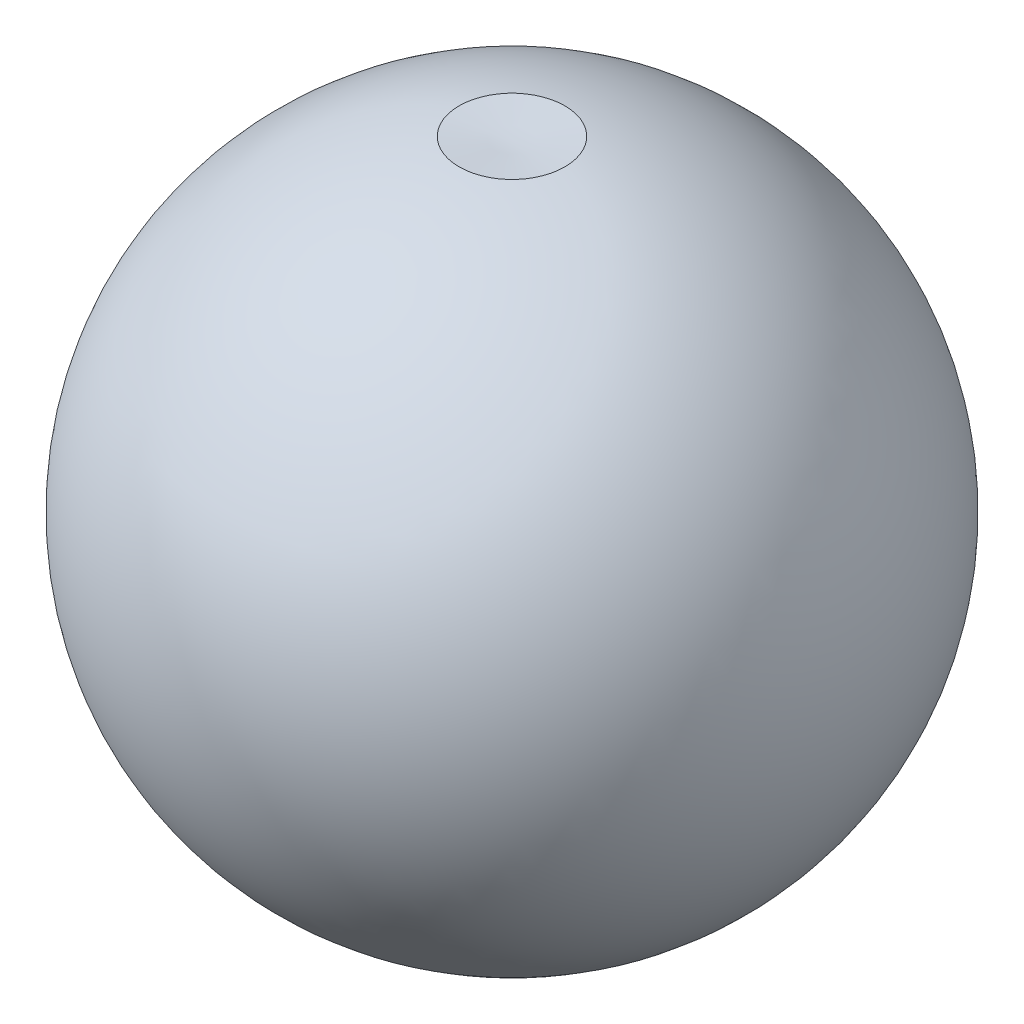
SolidWorks part; units mm, degrees
ref_plane "Plan de face" through (0, 0, 0) normal (0, 0, 1) x (1, 0, 0)
ref_plane "Plan de dessus" through (0, 0, 0) normal (0, 1, 0) x (1, 0, 0)
ref_plane "Plan de droite" through (0, 0, 0) normal (1, 0, 0) x (0, 0, -1)
sketch "Esquisse1" plane through (0, 0, 0) normal (0, 0, 1) x (1, 0, 0)
  line L0 (0, 29.5804) -> (0, -30)
  line L1 (0, 29.5804) -> (4.8753, 30)
  line L2 (0, 0) -> (7.1794, 0) construction
  line L3 (0, -30) -> (4.8753, -30)
  arc A1 (4.8753, -30) -> (4.8753, 30) centre (0, 0) ccw
  point P7 (0, 29.5804)
  dimension "D2" = 30
revolve "BASE" add sketch "Esquisse1" angle 360 about L0
